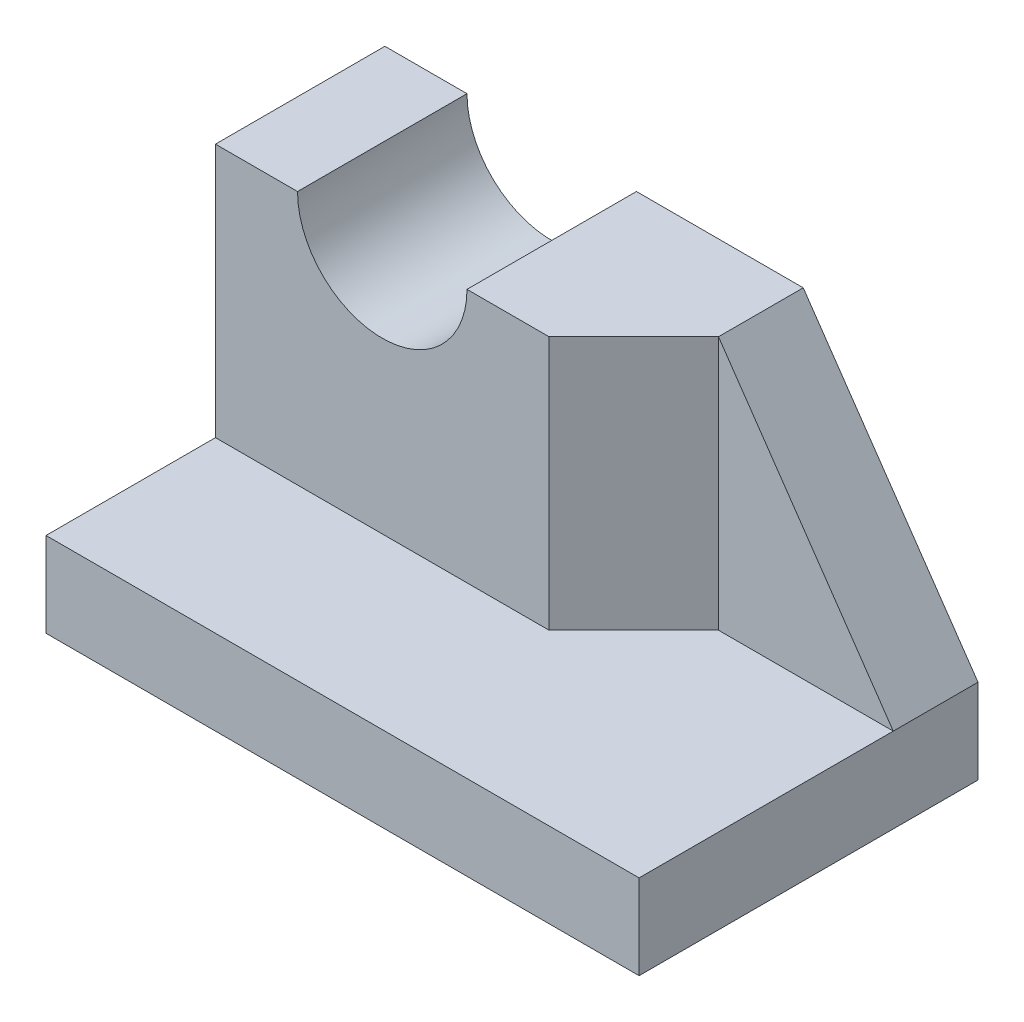
SolidWorks part; units mm, degrees
ref_plane "Front Plane" through (0, 0, 0) normal (0, 0, 1) x (1, 0, 0)
ref_plane "Top Plane" through (0, 0, 0) normal (0, 1, 0) x (1, 0, 0)
ref_plane "Right Plane" through (0, 0, 0) normal (1, 0, 0) x (0, 0, -1)
sketch "Sketch1" plane through (0, 0, 0) normal (0, 1, 0) x (1, 0, 0)
  line L1 (-35, 20) -> (35, 20)
  line L2 (-35, 20) -> (-35, -20)
  line L3 (-35, -20) -> (35, -20)
  line L4 (35, 20) -> (35, -20)
  line L5 (-35, 20) -> (35, -20) construction
  line L6 (-35, -20) -> (35, 20) construction
  point P0 (0, 0)
  dimension "D1" = 40
  dimension "D2" = 70
extrude "Boss-Extrude1" add sketch "Sketch1" along normal blind 10
sketch "Sketch2" plane through (0, 10, 0) normal (0, 1, 0) x (1, 0, 0)
  line L0 (-35, 20) -> (-35, 0)
  line L1 (-35, 20) -> (-35, -20) construction
  line L2 (-35, 0) -> (4.3728, 0)
  line L3 (4.3728, 0) -> (14.3728, 10)
  line L4 (14.3728, 10) -> (35, 10)
  line L5 (35, -20) -> (35, 20) construction
  line L6 (35, 10) -> (35, 20)
  line L7 (35, 20) -> (-35, 20)
  point P5 (24.6864, 10)
  dimension "D1" = 10
  dimension "D2" = 135
  dimension "D3" = 20
extrude "Boss-Extrude2" add sketch "Sketch2" along normal blind 30
sketch "Sketch3" plane through (0, 0, 0) normal (0, 0, 1) x (1, 0, 0)
  line L0 (-35, 40) -> (4.3728, 40) construction
  line L1 (-25.3136, 40) -> (-35, 40)
  line L2 (-35, 40) -> (-35, 0)
  line L3 (-35, 0) -> (35, 0)
  line L4 (35, 0) -> (35, 10)
  line L5 (35, 10) -> (14.3728, 40)
  line L6 (14.3728, 40) -> (-5.3136, 40)
  arc A0 (-25.3136, 40) -> (-5.3136, 40) centre (-15.3136, 40) ccw
  dimension "D1" = 20
extrude "Cut-Extrude1" cut sketch "Sketch3" against normal through all both and the other way through all flip side to cut
